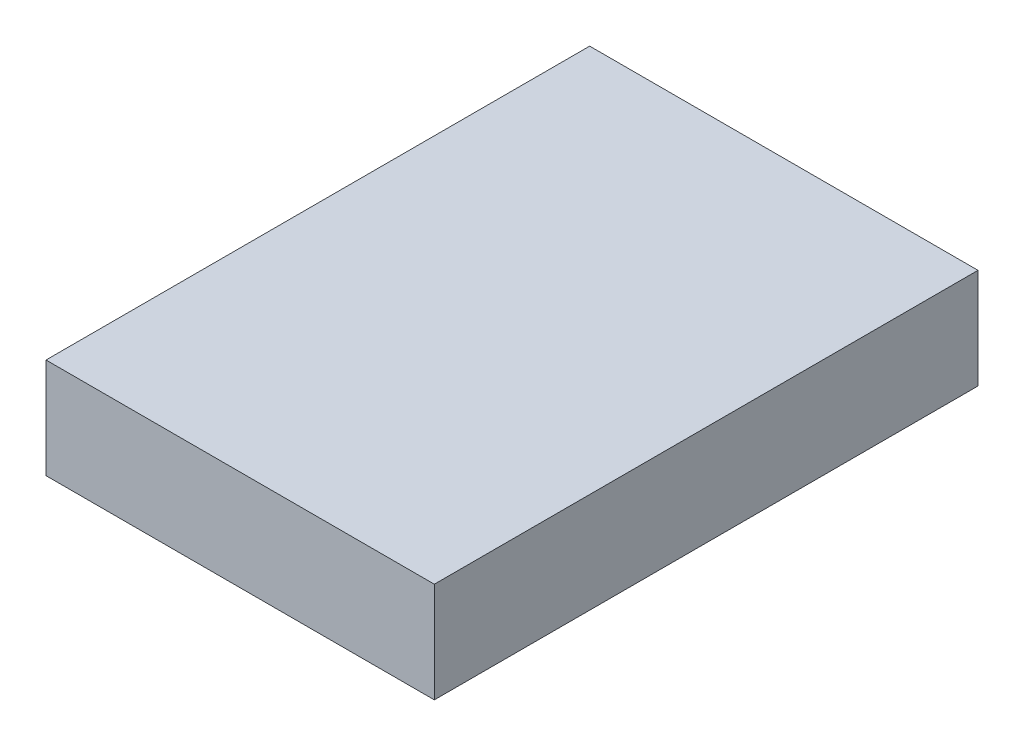
SolidWorks part; units mm, degrees
ref_plane "Front Plane" through (0, 0, 0) normal (0, 0, 1) x (1, 0, 0)
ref_plane "Top Plane" through (0, 0, 0) normal (0, 1, 0) x (1, 0, 0)
ref_plane "Right Plane" through (0, 0, 0) normal (1, 0, 0) x (0, 0, -1)
sketch "Sketch3" plane through (0, 0, 0) normal (0, 1, 0) x (1, 0, 0)
  line L1 (0, 0) -> (63.5, 0)
  line L2 (0, 0) -> (0, 88.9)
  line L3 (0, 88.9) -> (63.5, 88.9)
  line L4 (63.5, 0) -> (63.5, 88.9)
extrude "Boss-Extrude1" add sketch "Sketch3" along normal blind 16.383
